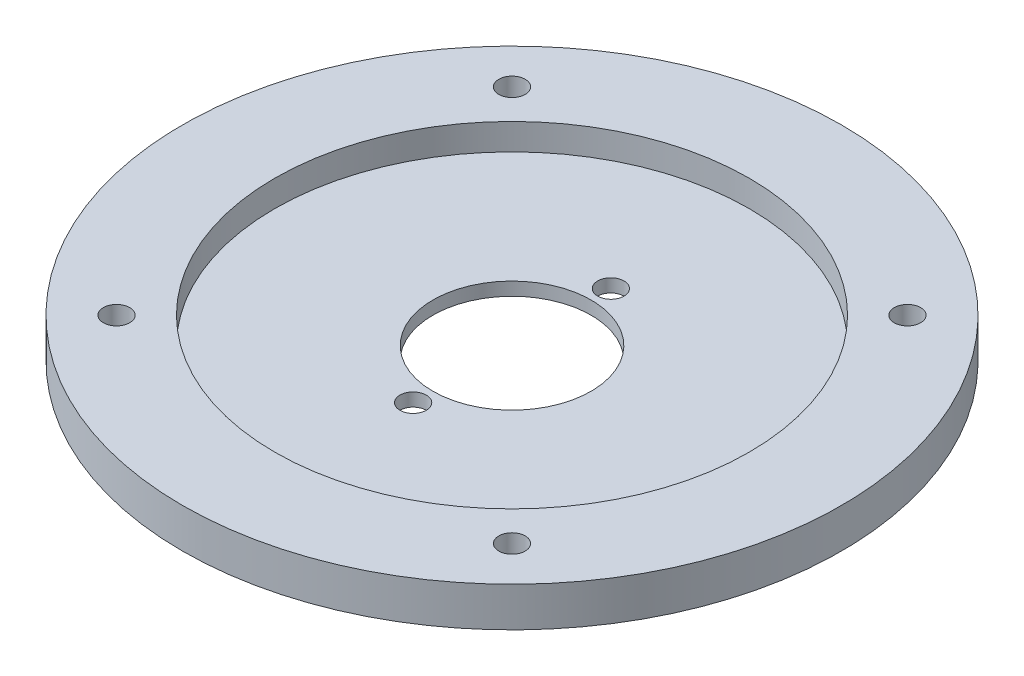
SolidWorks part; units mm, degrees
ref_plane "Front Plane" through (0, 0, 0) normal (0, 0, 1) x (1, 0, 0)
ref_plane "Top Plane" through (0, 0, 0) normal (0, 1, 0) x (1, 0, 0)
ref_plane "Right Plane" through (0, 0, 0) normal (1, 0, 0) x (0, 0, -1)
sketch "Sketch1" plane through (0, 0, 0) normal (0, 1, 0) x (1, 0, 0)
  circle A0 centre (0, 0) radius 25
  dimension "D1" = 50
extrude "Boss-Extrude1" add sketch "Sketch1" along normal blind 3
sketch "Sketch3" plane through (0, 3, 0) normal (0, 1, 0) x (1, 0, 0)
  line L0 (0, -7.5) -> (0, 7.5) construction
  circle A0 centre (0, 0) radius 6
  circle A1 centre (0, 7.5) radius 1
  circle A2 centre (0, -7.5) radius 1
  point P7 (0, 6.6493)
  point P8 (0, 8.5887)
  dimension "D1" = 12
  dimension "D2" = 2
  dimension "D3" = 2
  dimension "D4" = 15
extrude "Cut-Extrude1" cut sketch "Sketch3" against normal through all
sketch "Sketch4" plane through (0, 3, 0) normal (0, 1, 0) x (1, 0, 0)
  line L1 (-15, 15) -> (15, 15) construction
  line L2 (-15, 15) -> (-15, -15) construction
  line L3 (-15, -15) -> (15, -15) construction
  line L4 (15, 15) -> (15, -15) construction
  line L5 (-15, 15) -> (15, -15) construction
  line L6 (-15, -15) -> (15, 15) construction
  circle A0 centre (-15, 15) radius 1
  circle A1 centre (15, 15) radius 1
  circle A2 centre (15, -15) radius 1
  circle A3 centre (-15, -15) radius 1
  point P0 (0, 0)
  point P6 (0, 0)
  dimension "D2" = 2
  dimension "D3" = 4
  dimension "D1" = 30
extrude "Cut-Extrude2" cut sketch "Sketch4" against normal through all
chamfer "Chamfer1" distance 1 angle 45 4 edges at (-15, 0, -14) (15, 0, -14) (15, 0, 16) (-15, 0, 16)
sketch "Sketch5" plane through (0, 3, 0) normal (0, 1, 0) x (1, 0, 0)
  circle A0 centre (0, 0) radius 18
  dimension "D1" = 36
extrude "Cut-Extrude3" cut sketch "Sketch5" against normal blind 2
